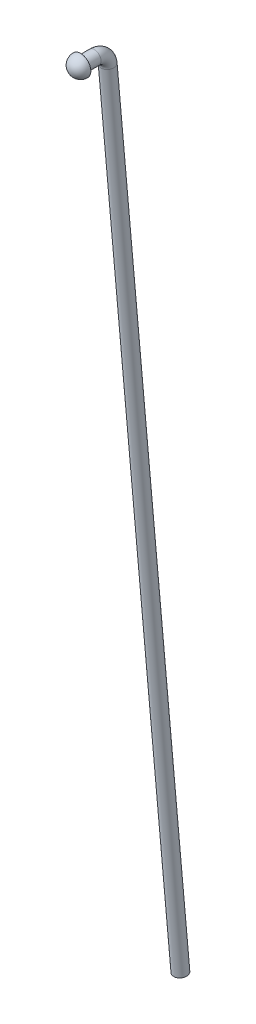
SolidWorks part; units mm, degrees
material "Alloy Steel"
ref_plane "Front Plane" through (0, 0, 0) normal (0, 0, 1) x (1, 0, 0)
ref_plane "Top Plane" through (0, 0, 0) normal (0, 1, 0) x (1, 0, 0)
ref_plane "Right Plane" through (0, 0, 0) normal (1, 0, 0) x (0, 0, -1)
sketch "Sketch2" plane through (0, 0, 0) normal (1, 0, 0) x (0, 0, -1)
  line L0 (0, 39.3673) -> (3.0934, 39.3673)
  line L1 (6.0818, 36.6314) -> (22.4239, -148.3014)
  arc A0 (3.0934, 39.3673) -> (6.0818, 36.6314) centre (3.0934, 36.3673) cw
  point P5 (5.84, 39.3673)
  dimension "D4" = 3
  dimension "D1" = 5.84
  dimension "D2" = 95.05
  dimension "D3" = 188.4
ref_plane "Plane1" through (0, 0, 0) normal (0, 0, 1) x (1, 0, 0)
sketch "Sketch3" plane through (0, 0, 0) normal (0, 0, 1) x (1, 0, 0)
  line L0 (0, 36.6314) -> (0, -148.3014) construction
  circle A0 centre (0, 39.3673) radius 1.5
  dimension "D1" = 3
sweep "Sweep1" add profiles "Sketch3" path "Sketch2"
sketch "Sketch4" plane through (0, 0, 0) normal (1, 0, 0) x (0, 0, -1)
  line L0 (0, 39.3673) -> (0, 41.6673)
  line L1 (0, 40.8673) -> (0, 37.8673) construction
  line L2 (-2.3, 39.3673) -> (0, 39.3673)
  arc A0 (0, 41.6673) -> (-2.3, 39.3673) centre (0, 39.3673) ccw
  dimension "D1" = 2.3
revolve "Revolve1" add sketch "Sketch4" angle 360 about L2
